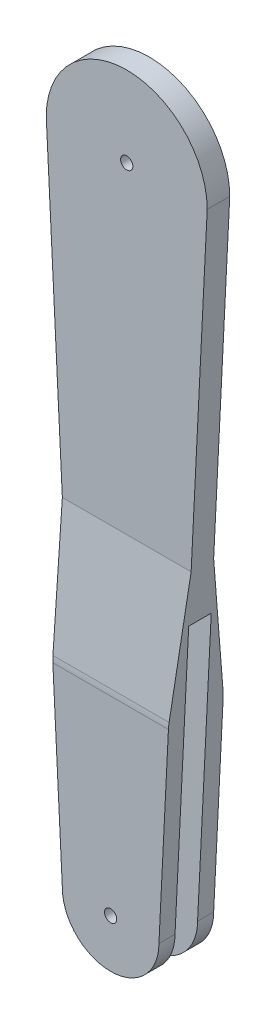
SolidWorks part; units mm, degrees
ref_plane "Front Plane" through (0, 0, 0) normal (0, 0, 1) x (1, 0, 0)
ref_plane "Top Plane" through (0, 0, 0) normal (0, 1, 0) x (1, 0, 0)
ref_plane "Right Plane" through (0, 0, 0) normal (1, 0, 0) x (0, 0, -1)
sketch "Sketch2" plane through (0, 0, 0) normal (0, 0, 1) x (1, 0, 0)
  line L1 (15, -200) -> (25, 0)
  line L2 (-15, -200) -> (-25, 0)
  line L3 (0, -200) -> (0, -397.2479)
  line L4 (0, -170) -> (0, -200)
  arc A2 (25, 0) -> (-25, 0) centre (0, 0) ccw
  arc A4 (-15, -200) -> (15, -200) centre (0, -200) ccw
  dimension "D1" = 200
  dimension "D2" = 50
  dimension "D3" = 15
extrude "Boss-Extrude1" add sketch "Sketch2" along normal blind 7
ref_plane "Plane1" through (0, 0, 3.5) normal (0, 0, 1) x (1, 0, 0)
sketch "Sketch6" plane through (0, 0, 7) normal (0, 0, 1) x (1, 0, 0)
  circle A0 centre (0, -200) radius 2.25
  dimension "D1" = 4.5
extrude "Cut-Extrude4" cut sketch "Sketch6" against normal blind 25
ref_plane "Plane2" through (0, 0, 0) normal (-1, 0, 0) x (0, 0, 1)
sketch "Sketch9" plane through (0, 0, 0) normal (-1, 0, 0) x (0, 0, 1)
  line L0 (0, -200) -> (0, -215)
  line L1 (0, -200) -> (0, -215) construction
  line L2 (0, -215) -> (-5, -215)
  line L3 (-5, -215) -> (-5, -140)
  line L4 (-5, -140) -> (0, -100)
  line L5 (0, -200) -> (0, 0) construction
  line L6 (0, -200) -> (0, -100)
  dimension "D1" = 15
  dimension "D2" = 5
  dimension "D3" = 75
extrude "Boss-Extrude2" add sketch "Sketch9" along normal blind 22 and the other way blind 21
sketch "Sketch10" plane through (0, 0, 7) normal (0, 0, 1) x (1, 0, 0)
  line L0 (20, -100) -> (21, -100)
  line L1 (15, -200) -> (25, 0) construction
  line L2 (21, -100) -> (21, -215)
  line L3 (21, -215) -> (-22, -215)
  line L4 (-22, -215) -> (-22, -100)
  line L5 (-22, -100) -> (-20, -100)
  line L6 (-15, -200) -> (-25, 0) construction
  line L7 (-20, -100) -> (-15, -200)
  line L8 (15, -200) -> (20, -100)
  arc A0 (-15, -200) -> (15, -200) centre (0, -200) ccw
  arc M10 (-15, -200) -> (15, -200) centre (0, -200) ccw
  line M11 (15, -200) -> (25, 0)
  line M13 (-25, 0) -> (-15, -200)
extrude "Cut-Extrude5" cut sketch "Sketch10" against normal mid plane 56 contours L3 L2 L0 M11 M10 | L5 L4 L3 M10 M13
fillet "Fillet1" radius 15 1 edges at (0, -140, -5)
mirror "Mirror1" about plane through (0, 0, 3.5) normal (0, 0, 1) of "Fillet1", "Boss-Extrude2"
mirror "Mirror2" about plane through (0, 0, 3.5) normal (0, 0, 1) of "Cut-Extrude5"
sketch "Sketch12" plane through (0, 0, 0) normal (-1, 0, 0) x (0, 0, 1)
  line L0 (-5, -215) -> (12, -215) construction
  line L1 (0, -215) -> (7, -215)
  line L2 (0, -215) -> (0, -115)
  line L3 (0, -115) -> (7, -115)
  line L4 (7, -215) -> (7, -115)
  line L5 (12, -215) -> (12, -200) construction
  dimension "D1" = 7
  dimension "D2" = 5
  dimension "D3" = 100
extrude "Cut-Extrude6" cut sketch "Sketch12" along normal mid plane 49
sketch "Sketch13" plane through (0, 0, -5) normal (0, 0, -1) x (-1, 0, 0)
  circle A0 centre (0, -200) radius 1.9
  dimension "D1" = 3.8
extrude "Cut-Extrude7" cut sketch "Sketch13" against normal mid plane 49
sketch "Sketch14" plane through (0, 0, 0) normal (0, 0, -1) x (-1, 0, 0)
  circle A0 centre (0, 0) radius 1.9
  dimension "D1" = 3.8
extrude "Cut-Extrude8" cut sketch "Sketch14" against normal blind 7
